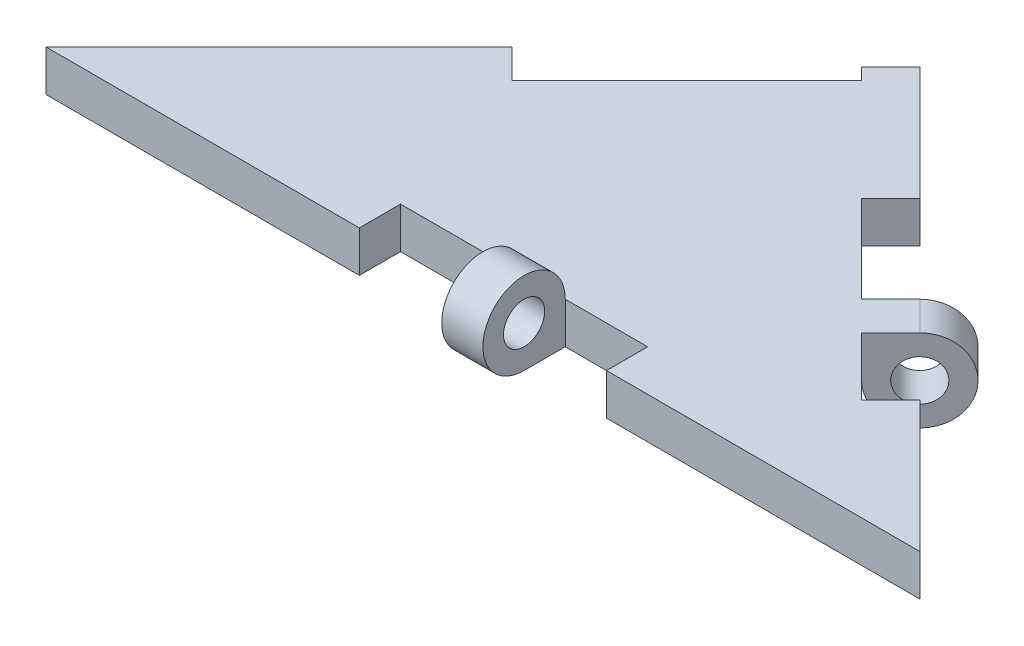
SolidWorks part; units mm, degrees
material "PET"
ref_plane "Front Plane" through (0, 0, 0) normal (0, 0, 1) x (1, 0, 0)
ref_plane "Top Plane" through (0, 0, 0) normal (0, 1, 0) x (1, 0, 0)
ref_plane "Right Plane" through (0, 0, 0) normal (1, 0, 0) x (0, 0, -1)
other "Center of Mass"
sketch "Sketch1" plane through (0, 0, 0) normal (0, 1, 0) x (1, 0, 0)
  line L0 (-53.033, 0) -> (53.033, 0)
  line L1 (-53.033, 0) -> (0, 53.033)
  line L2 (0, 53.033) -> (53.033, 0)
  dimension "D1" = 75
extrude "Boss-Extrude1" add sketch "Sketch1" along normal blind 5
sketch "Sketch2" plane through (0, 5, 0) normal (0, 1, 0) x (1, 0, 0)
  line L0 (-15, 0) -> (15, 0)
  line L1 (-15, 0) -> (-15, 5)
  line L2 (15, 0) -> (15, 5)
  line L3 (-15, 5) -> (15, 5)
  line L4 (-53.033, 0) -> (53.033, 0) construction
  line L5 (0, 0) -> (0, 8.7982) construction
  line L6 (-3.5355, 49.4975) -> (-24.7487, 28.2843)
  line L7 (-3.5355, 49.4975) -> (0, 45.9619)
  line L8 (-24.7487, 28.2843) -> (-21.2132, 24.7487)
  line L9 (0, 45.9619) -> (-21.2132, 24.7487)
  line L10 (0, 53.033) -> (-53.033, 0) construction
  line L11 (53.033, 0) -> (0, 53.033) construction
  dimension "D1" = 5
  dimension "D2" = 30
  dimension "D3" = 5
  dimension "D4" = 30
  dimension "D5" = 35
extrude "Cut-Extrude1" cut sketch "Sketch2" against normal blind 5
sketch "Sketch3" plane through (0, 0, 0) normal (0, -1, 0) x (1, 0, 0)
  line L0 (15.9099, -37.1231) -> (37.1231, -15.9099)
  line L1 (15.9099, -37.1231) -> (12.3744, -33.5876)
  line L2 (37.1231, -15.9099) -> (33.5876, -12.3744)
  line L3 (12.3744, -33.5876) -> (33.5876, -12.3744)
  line L4 (53.033, 0) -> (0, -53.033) construction
  line L5 (26.5165, -26.5165) -> (21.478, -21.478) construction
  dimension "D1" = 5
  dimension "D2" = 30
extrude "Cut-Extrude2" cut sketch "Sketch3" against normal blind 5
sketch "Sketch5" plane through (15, 0, 0) normal (-1, 0, 0) x (0, 0, 1)
  circle A0 centre (0, 5) radius 5
  circle A1 centre (0, 5) radius 2.5
  dimension "D1" = 5
extrude "Boss-Extrude2" add sketch "Sketch5" along normal blind 5 from offset 10
sketch "Sketch6" plane through (10.6066, 0, 10.6066) normal (-0.7071, 0, -0.7071) x (-0.7071, 0, 0.7071)
  circle A0 centre (-37.5, 0) radius 5
  circle A1 centre (-37.5, 0) radius 2.5
  dimension "D1" = 5
extrude "Boss-Extrude3" add sketch "Sketch6" along normal blind 5 from offset 10
sketch "Sketch7" plane through (0, 0, 0) normal (0, -1, 0) x (1, 0, 0)
  line L0 (0, -53.033) -> (-23.4109, -29.6221)
  line L1 (0, -53.033) -> (2.1213, -50.9117)
  line L2 (-23.4109, -29.6221) -> (-21.2896, -27.5008)
  line L3 (2.1213, -50.9117) -> (-21.2896, -27.5008)
  dimension "D1" = 3
extrude "Cut-Extrude3" cut sketch "Sketch7" against normal blind 10 contours L3 L2 L0 L1
chamfer "Chamfer1" [suppressed] distance 2 angle 45
other "Center of Mass Reference Point1"
